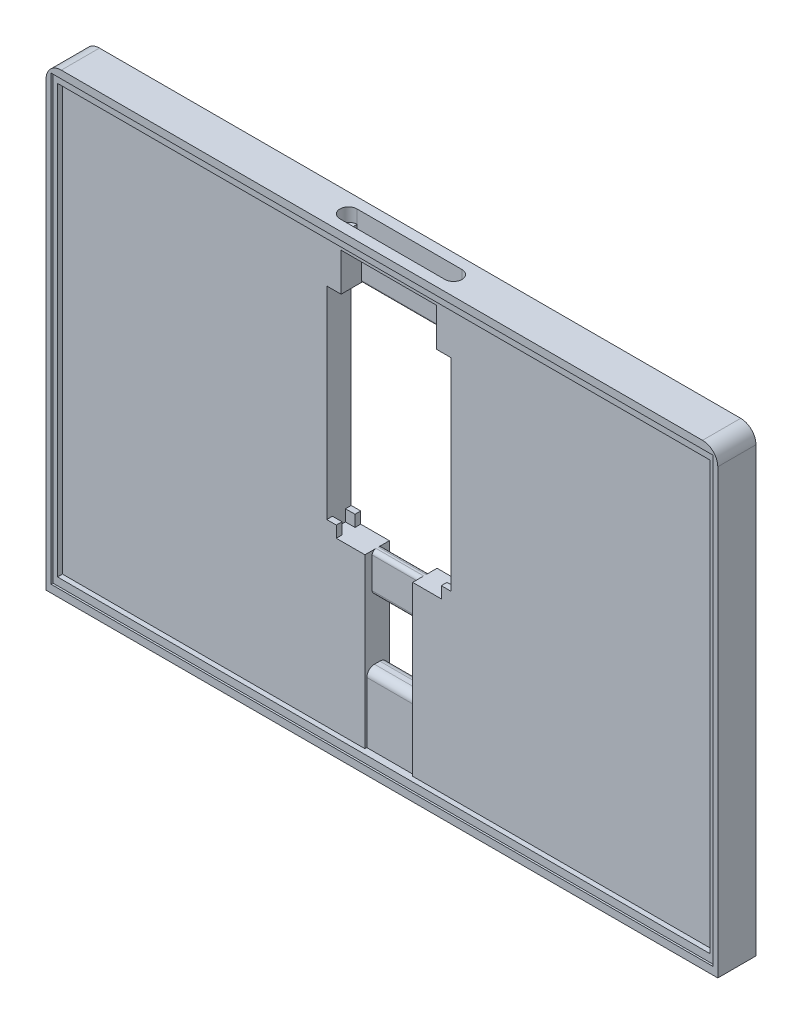
SolidWorks part; units mm, degrees
ref_plane "前视基准面" through (0, 0, 0) normal (0, 0, 1) x (1, 0, 0)
ref_plane "上视基准面" through (0, 0, 0) normal (0, 1, 0) x (1, 0, 0)
ref_plane "右视基准面" through (0, 0, 0) normal (1, 0, 0) x (0, 0, -1)
other "Configuration Table"
sketch "草图1" plane through (0, 0, 0) normal (0, 0, 1) x (1, 0, 0)
  line L0 (-88, 60) -> (-88, -60)
  line L1 (-88, -60) -> (88, -60)
  line L2 (88, -60) -> (88, 60)
  line L3 (88, 60) -> (-88, 60)
  line L4 (0, 145.8225) -> (0, -134.4269) construction
  line L5 (-152.9976, 0) -> (171.9904, 0) construction
  dimension "D1" = 176
  dimension "D2" = 120
extrude "凸台-拉伸1" add sketch "草图1" along normal blind 10
sketch "草图2" plane through (0, 0, 10) normal (0, 0, 1) x (1, 0, 0)
  line L0 (-111.1919, 0) -> (116.8836, 0) construction
  line L1 (0, 67.9619) -> (0, -74.6023) construction
  line L3 (-85.5, 56) -> (85.5, 56)
  line L4 (-85.5, 56) -> (-85.5, -56)
  line L5 (-85.5, -56) -> (85.5, -56)
  line L6 (85.5, 56) -> (85.5, -56)
  line L7 (-85.5, 56) -> (85.5, -56) construction
  line L8 (-85.5, -56) -> (85.5, 56) construction
  point P5 (0, 0)
  dimension "D1" = 171
  dimension "D2" = 112
extrude "切除-拉伸1" cut sketch "草图2" against normal blind 1.8
sketch "草图3" plane through (0, 0, 0) normal (0, 0, -1) x (-1, 0, 0)
  line L0 (-109.5657, 0) -> (110.3788, 0) construction
  line L1 (0, 67.4198) -> (0, -75.1443) construction
  line L3 (-85.5, 56) -> (85.5, 56)
  line L4 (-85.5, 56) -> (-85.5, -56)
  line L5 (-85.5, -56) -> (85.5, -56)
  line L6 (85.5, 56) -> (85.5, -56)
  line L7 (-85.5, 56) -> (85.5, -56) construction
  line L8 (-85.5, -56) -> (85.5, 56) construction
  point P5 (0, 0)
  dimension "D1" = 171
  dimension "D2" = 112
extrude "切除-拉伸2" cut sketch "草图3" against normal blind 1.8
sketch "草图5" plane through (0, 0, 0) normal (0, 0, -1) x (-1, 0, 0)
  line L1 (-86.7, 58) -> (86.7, 58)
  line L2 (-86.7, 58) -> (-86.7, -58)
  line L3 (-86.7, -58) -> (86.7, -58)
  line L4 (86.7, 58) -> (86.7, -58)
  line L5 (-86.7, 58) -> (86.7, -58) construction
  line L6 (-86.7, -58) -> (86.7, 58) construction
  point P0 (0, 0)
  dimension "D1" = 173.4
  dimension "D2" = 116
extrude "切除-拉伸3" cut sketch "草图5" against normal blind 0.5
sketch "草图6" plane through (0, 0, 10) normal (0, 0, 1) x (1, 0, 0)
  line L1 (-86.7, 58) -> (86.7, 58)
  line L2 (-86.7, 58) -> (-86.7, -58)
  line L3 (-86.7, -58) -> (86.7, -58)
  line L4 (86.7, 58) -> (86.7, -58)
  line L5 (-86.7, 58) -> (86.7, -58) construction
  line L6 (-86.7, -58) -> (86.7, 58) construction
  point P0 (0, 0)
  dimension "D1" = 173.4
  dimension "D2" = 116
extrude "切除-拉伸4" cut sketch "草图6" against normal blind 0.5
sketch "草图7" plane through (0, 0, 1.8) normal (0, 0, -1) x (-1, 0, 0)
  line L0 (0, 28.0765) -> (0, -41.7057) construction
  line L1 (-16.25, 44) -> (16.25, 44)
  line L2 (-16.25, 44) -> (-16.25, -12)
  line L3 (-16.25, -12) -> (16.25, -12)
  line L4 (16.25, 44) -> (16.25, -12)
  line L5 (-16.25, 44) -> (16.25, -12) construction
  line L6 (-16.25, -12) -> (16.25, 44) construction
  line L7 (-86.7, -58) -> (86.7, -58) construction
  point P0 (0, 16)
  dimension "D1" = 32.5
  dimension "D2" = 56
  dimension "D3" = 46
extrude "切除-拉伸5" cut sketch "草图7" against normal through all
sketch "草图8" plane through (0, 0, 1.8) normal (0, 0, -1) x (-1, 0, 0)
  line L0 (0, 36.1154) -> (0, -67.2843) construction
  line L1 (-6.25, -12) -> (-6.25, -56)
  line L2 (-16.25, -12) -> (16.25, -12) construction
  line L3 (-85.5, -56) -> (85.5, -56) construction
  line L4 (-6.25, -56) -> (6.25, -56)
  line L5 (6.25, -56) -> (6.25, -12)
  line L6 (6.25, -12) -> (-6.25, -12)
  dimension "D1" = 12.5
extrude "切除-拉伸6" cut sketch "草图8" against normal blind 0.5
sketch "草图9" plane through (0, 0, 8.2) normal (0, 0, 1) x (1, 0, 0)
  line L0 (0, 18.0916) -> (0, -73.9247) construction
  line L1 (-6.25, -12) -> (-6.25, -56)
  line L2 (-16.25, -12) -> (16.25, -12) construction
  line L3 (85.5, -56) -> (-85.5, -56) construction
  line L4 (-6.25, -56) -> (6.25, -56)
  line L5 (-85.5, -56) -> (85.5, -56) construction
  line L6 (6.25, -56) -> (6.25, -12)
  line L7 (6.25, -12) -> (-6.25, -12)
  dimension "D1" = 12.5
extrude "切除-拉伸7" cut sketch "草图9" against normal blind 0.5
sketch "草图10" plane through (0, 0, 8.2) normal (0, 0, 1) x (1, 0, 0)
  line L0 (0, 67.0133) -> (0, 14.2971) construction
  line L1 (-12.5, 56) -> (-12.5, 44)
  line L2 (-85.5, 56) -> (85.5, 56) construction
  line L3 (16.25, 44) -> (-16.25, 44) construction
  line L4 (-12.5, 44) -> (12.5, 44)
  line L5 (12.5, 44) -> (12.5, 56)
  line L6 (12.5, 56) -> (-12.5, 56)
  dimension "D1" = 25
extrude "切除-拉伸8" cut sketch "草图10" against normal blind 0.8
sketch "草图11" plane through (0, 0, 1.8) normal (0, 0, -1) x (-1, 0, 0)
  line L0 (0, 66.8778) -> (0, 24.5964) construction
  line L1 (-33.5, 56) -> (-33.5, 44)
  line L2 (85.5, 56) -> (-85.5, 56) construction
  line L3 (16.25, 44) -> (-16.25, 44) construction
  line L4 (-33.5, 44) -> (33.5, 44)
  line L5 (33.5, 44) -> (33.5, 56)
  line L6 (33.5, 56) -> (-33.5, 56)
  dimension "D1" = 67
sketch "草图13" plane through (0, 60, 0) normal (0, 1, 0) x (1, 0, 0)
  line L0 (0, 12.7154) -> (0, -17.2798) construction
  line L4 (-13.75, -5) -> (13.75, -5) construction
  line L5 (-13.75, -2.75) -> (13.75, -2.75)
  line L6 (-13.75, -7.25) -> (13.75, -7.25)
  line L7 (88, -10) -> (88, 0) construction
  line L8 (88, -5) -> (-97.094, -5) construction
  arc A2 (-13.75, -2.75) -> (-13.75, -7.25) centre (-13.75, -5) ccw
  arc A3 (13.75, -7.25) -> (13.75, -2.75) centre (13.75, -5) ccw
  point P10 (0, -5)
  point P19 (-16, -5)
  point P20 (16, -5)
  dimension "D2" = 32
  dimension "D4" = 4.5
extrude "切除-拉伸10" cut sketch "草图13" against normal blind 6
sketch "草图14" plane through (-88, 0, 0) normal (-1, 0, 0) x (0, 0, 1)
  line L0 (10, 60) -> (10, -60) construction
  line L1 (3.9552, 54.3709) -> (3.9552, 60)
  line L2 (10, 60) -> (0, 60) construction
  line L3 (3.9552, 60) -> (6.3387, 60)
  line L4 (10, 53.3261) -> (10, 48.3261)
  line L5 (6.3387, 60) -> (6.3387, 57.2188)
  arc A0 (3.9552, 54.3709) -> (10, 48.3261) centre (10, 54.3709) ccw
  arc A2 (6.3387, 57.2188) -> (10, 53.3261) centre (12.9409, 59.7605) ccw
  dimension "D1" = 5
ref_plane "基准面1" through (0, 0, 5) normal (0, 0, 1) x (1, 0, 0)
sketch "草图16" plane through (-88, 0, 0) normal (-1, 0, 0) x (0, 0, 1)
  line L0 (0, -60) -> (-14.0954, -65.1303)
  line L1 (10, -60) -> (24.0954, -65.1303)
  line L2 (10, 60) -> (10, -60) construction
  line L3 (0, 60) -> (0, -60) construction
  line L4 (-14.0954, -65.1303) -> (-14.0954, -67.3303)
  line L5 (24.0954, -65.1303) -> (24.0954, -67.3303)
  line L6 (24.0954, -67.3303) -> (-14.0954, -67.3303)
  line L7 (0, -60) -> (10, -60)
  dimension "D1" = 15
  dimension "D2" = 15
  dimension "D3" = 110
  dimension "D4" = 110
  dimension "D5" = 2.2
fillet "圆角1" radius 4 1 edges at (-88, 60, 5)
fillet "圆角2" radius 4 1 edges at (88, 60, 5)
ref_plane "基准面2" through (-16.25, 0, 0) normal (1, 0, 0) x (0, 0, -1)
sketch "草图18" plane through (-16.25, 0, 0) normal (1, 0, 0) x (0, 0, -1)
  line L0 (-1.8, -9) -> (-3.3, -9)
  line L1 (-1.8, -12) -> (-1.8, 44) construction
  line L2 (-3.3, -9) -> (-3.3, -12)
  line L3 (-8.2, -12) -> (-1.8, -12) construction
  line L4 (-3.3, -12) -> (-1.8, -12)
  line L5 (-1.8, -12) -> (-1.8, -9)
  line L6 (-8.2, -9) -> (-8.2, -12)
  line L7 (-8.2, 44) -> (-8.2, -12) construction
  line L8 (-8.2, -12) -> (-6.7, -12)
  line L9 (-6.7, -12) -> (-6.7, -9)
  line L10 (-6.7, -9) -> (-8.2, -9)
  dimension "D1" = 1.5
  dimension "D2" = 1.5
  dimension "D3" = 3
  dimension "D4" = 3
extrude "凸台-拉伸3" add sketch "草图18" along normal blind 2.5
ref_plane "基准面3" through (16.25, 0, 0) normal (-1, 0, 0) x (0, 0, 1)
sketch "草图19" plane through (16.25, 0, 0) normal (-1, 0, 0) x (0, 0, 1)
  line L0 (1.8, -8.7196) -> (2.6, -8.7196)
  line L1 (1.8, 44) -> (1.8, -12) construction
  line L2 (2.6, -8.7196) -> (2.6, -12)
  line L3 (8.2, -12) -> (1.8, -12) construction
  line L4 (2.6, -12) -> (1.8, -12)
  line L5 (1.8, -12) -> (1.8, -8.7196)
  dimension "D1" = 0.8
sketch "草图20" plane through (16.25, 0, 0) normal (-1, 0, 0) x (0, 0, 1)
  line L0 (8.2, -9) -> (6.7, -9)
  line L1 (8.2, -12) -> (8.2, 44) construction
  line L2 (6.7, -9) -> (6.7, -12)
  line L3 (8.2, -12) -> (1.8, -12) construction
  line L4 (6.7, -12) -> (8.2, -12)
  line L5 (8.2, -12) -> (8.2, -9)
  line L6 (1.8, -9) -> (3.3, -9)
  line L7 (1.8, 44) -> (1.8, -12) construction
  line L8 (3.3, -9) -> (3.3, -12)
  line L9 (3.3, -12) -> (1.8, -12)
  line L10 (1.8, -12) -> (1.8, -9)
  dimension "D1" = 1.5
  dimension "D2" = 1.5
  dimension "D3" = 3
extrude "凸台-拉伸4" add sketch "草图20" along normal blind 2.5
ref_plane "基准面5" through (0, 0, 2.3) normal (0, 0, -1) x (-1, 0, 0)
sketch "草图21" plane through (0, 0, 2.3) normal (0, 0, -1) x (-1, 0, 0)
  line L0 (-6.25, -22.083) -> (-6.25, -38.083)
  line L1 (-6.25, -12) -> (-6.25, -56) construction
  line L2 (-6.25, -12) -> (-6.25, -56) construction
  line L3 (-6.25, -38.083) -> (6.25, -38.083)
  line L4 (6.25, -56) -> (6.25, -12) construction
  line L5 (6.25, -38.083) -> (6.25, -22.083)
  line L6 (6.25, -22.083) -> (-6.25, -22.083)
  dimension "D1" = 16
extrude "切除-拉伸12" cut sketch "草图21" against normal through all
ref_plane "基准面6" through (0, 0, 7.4) normal (0, 0, 1) x (1, 0, 0)
sketch "草图22" plane through (0, 0, 7.4) normal (0, 0, 1) x (1, 0, 0)
  line L1 (-12.5, 54) -> (12.5, 54)
  line L3 (12.5, 44) -> (12.5, 56) construction
  line L6 (-12.5, 54) -> (-12.5, 44)
  line L7 (-12.5, 56) -> (-12.5, 44) construction
  line L14 (12.5, 54) -> (12.5, 44)
  line L15 (12.5, 44) -> (-12.5, 44)
  dimension "D1" = 10
extrude "切除-拉伸13" cut sketch "草图22" against normal blind 4.5
ref_plane "基准面7" through (0, 0, 7.4) normal (0, 0, 1) x (1, 0, 0)
sketch "草图23" plane through (0, 0, 7.4) normal (0, 0, 1) x (1, 0, 0)
  line L0 (-12.5, 56) -> (-12.5, 54)
  line L1 (-12.5, 54) -> (12.5, 54)
  line L2 (12.5, 54) -> (12.5, 56)
  line L3 (12.5, 56) -> (-12.5, 56)
extrude "凸台-拉伸5" add sketch "草图23" along normal blind 0.8
fillet "圆角15" radius 0.5 1 edges at (0, 54, 7.25)
ref_plane "基准面14" through (0, 54, 0) normal (0, 1, 0) x (1, 0, 0)
sketch "草图24" plane through (0, 54, 0) normal (0, 1, 0) x (1, 0, 0)
  line L0 (-13.75, -2.75) -> (-13.75, -7.25) construction
  line L1 (-13.75, -2.75) -> (-13.75, -7.25)
  line L2 (13.75, -2.75) -> (13.75, -7.25) construction
  line L3 (13.75, -2.75) -> (13.75, -7.25)
  arc A1 (-13.75, -2.75) -> (-13.75, -7.25) centre (-13.75, -5) ccw construction
  arc A2 (-13.75, -2.75) -> (-13.75, -7.25) centre (-13.75, -5) ccw
  arc A3 (13.75, -7.25) -> (13.75, -2.75) centre (13.75, -5) ccw construction
  arc A4 (13.75, -7.25) -> (13.75, -2.75) centre (13.75, -5) ccw construction
  arc A5 (13.75, -7.25) -> (13.75, -2.75) centre (13.75, -5) ccw
extrude "凸台-拉伸6" add sketch "草图24" along normal blind 2.5
ref_plane "基准面15" through (0, 0, 7.7) normal (0, 0, 1) x (1, 0, 0)
sketch "草图25" plane through (0, 0, 7.7) normal (0, 0, 1) x (1, 0, 0)
  line L0 (-6.25, -12) -> (-6.25, -22.083)
  line L1 (-6.25, -12) -> (-6.25, -56) construction
  line L2 (-6.25, -12) -> (-6.25, -22.083) construction
  line L3 (-6.25, -22.083) -> (6.25, -22.083)
  line L4 (6.25, -22.083) -> (6.25, -12)
  line L5 (6.25, -12) -> (-6.25, -12)
extrude "切除-拉伸14" cut sketch "草图25" against normal blind 1.4
ref_plane "基准面16" through (0, 0, 2.3) normal (0, 0, -1) x (-1, 0, 0)
sketch "草图26" plane through (0, 0, 2.3) normal (0, 0, -1) x (-1, 0, 0)
  line L0 (-6.25, -12) -> (-6.25, -22.083)
  line L1 (-6.25, -22.083) -> (6.25, -22.083)
  line L2 (6.25, -22.083) -> (6.25, -12)
  line L3 (6.25, -12) -> (-6.25, -12)
extrude "切除-拉伸15" cut sketch "草图26" against normal blind 1.4
fillet "圆角16" radius 1 1 edges at (0, -22.083, 3.7)
fillet "圆角17" radius 1 1 edges at (0, -12, 3.7)
fillet "圆角18" radius 1 1 edges at (0, -12, 6.3)
fillet "圆角19" radius 1 1 edges at (0, -22.083, 6.3)
fillet "圆角21" radius 2 1 edges at (0, -38.083, 7.7)
fillet "圆角22" radius 2 1 edges at (0, -38.083, 2.3)
ref_plane "基准面17" through (-88, 0, 0) normal (-1, 0, 0) x (0, 0, 1)
ref_plane "基准面18" through (0, -60, 0) normal (0, -1, 0) x (-1, 0, 0)
sketch "草图28" plane through (0, -60, 0) normal (0, -1, 0) x (-1, 0, 0)
  line L0 (-88, -5) -> (90.5933, -5) construction
  line L1 (-88, -10) -> (-88, 0) construction
  line L2 (0, 32.1995) -> (0, -32.8488) construction
  circle A0 centre (-72, -5) radius 2.75
  circle A1 centre (-38, -5) radius 2.75
  circle A2 centre (38, -5) radius 2.75
  circle A3 centre (72, -5) radius 2.75
  dimension "D1" = 5.5
  dimension "D2" = 5.5
  dimension "D3" = 5.5
  dimension "D4" = 5.5
  dimension "D5" = 38
  dimension "D6" = 38
  dimension "D7" = 72
  dimension "D8" = 72
extrude "切除-拉伸16" cut sketch "草图28" against normal blind 5.5
fillet "圆角23" radius 0.5 1 edges at (0, 44, 2.9)
